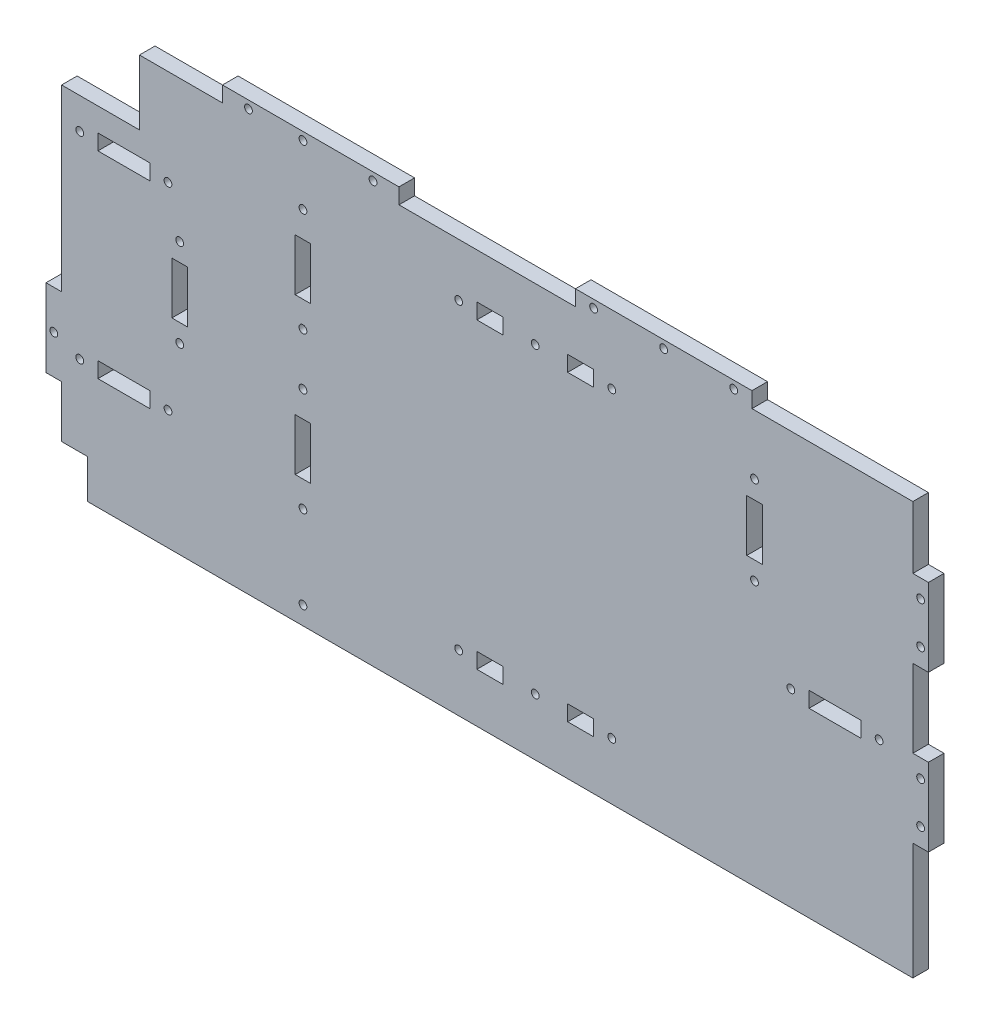
SolidWorks part; units mm, degrees
ref_plane "Plan de face" through (0, 0, 0) normal (0, 0, 1) x (1, 0, 0)
ref_plane "Plan de dessus" through (0, 0, 0) normal (0, 1, 0) x (1, 0, 0)
ref_plane "Plan de droite" through (0, 0, 0) normal (1, 0, 0) x (0, 0, -1)
sketch "Esquisse1" plane through (0, 0, 0) normal (0, 0, 1) x (1, 0, 0)
  line L1 (0, 0) -> (-340, 0)
  line L2 (0, 0) -> (0, 165)
  line L3 (0, 165) -> (-340, 165)
  line L4 (-340, 0) -> (-340, 165)
  dimension "D1" = 165
  dimension "D2" = 340
extrude "Boss.-Extru.1" add sketch "Esquisse1" along normal blind 6
sketch "Esquisse2" plane through (0, 0, 6) normal (0, 0, 1) x (1, 0, 0)
  line L0 (0, 0) -> (0, 165) construction
  line L1 (0, 165) -> (-340, 165) construction
  line L2 (0, 165) -> (0, 135)
  line L4 (0, 135) -> (-6, 135)
  line L5 (-6, 159) -> (-6, 135)
  line L6 (-340, 165) -> (-272, 165)
  line L7 (-340, 165) -> (-340, 65)
  line L8 (-340, 65) -> (-334, 65)
  line L9 (-334, 159) -> (-334, 65)
  line L10 (-70, 129) -> (-64, 129)
  line L11 (-70, 129) -> (-70, 109)
  line L12 (-70, 109) -> (-64, 109)
  line L13 (-334, 159) -> (-272, 159)
  line L14 (-272, 165) -> (-272, 159)
  line L15 (-204, 165) -> (-136, 165)
  line L16 (-204, 165) -> (-204, 159)
  line L17 (-204, 159) -> (-136, 159)
  line L18 (0, 0) -> (0, 165) construction
  line L19 (0, 0) -> (-6, 0)
  line L20 (0, 0) -> (0, 45)
  line L21 (0, 45) -> (-6, 45)
  line L22 (-136, 165) -> (-136, 159)
  line L23 (0, 165) -> (-68, 165)
  line L24 (-340, 0) -> (-334, 0)
  line L25 (-6, 159) -> (-68, 159)
  line L26 (-68, 165) -> (-68, 159)
  line L27 (-64, 129) -> (-64, 109)
  line L28 (-6, 0) -> (-6, 45)
  line L29 (0, 105) -> (-6, 105)
  line L30 (0, 105) -> (0, 75)
  line L31 (0, 75) -> (-6, 75)
  line L32 (-6, 105) -> (-6, 75)
  line L33 (-340, 0) -> (-340, 35)
  line L34 (-340, 35) -> (-334, 35)
  line L35 (-334, 0) -> (-334, 35)
  line L36 (-26, 76) -> (-46, 76)
  line L37 (-26, 76) -> (-26, 70)
  line L38 (-26, 70) -> (-46, 70)
  line L39 (-46, 76) -> (-46, 70)
  dimension "D3" = 6
  dimension "D4" = 62
  dimension "D5" = 68
  dimension "D6" = 68
  dimension "D7" = 24
  dimension "D8" = 6
  dimension "D9" = 70
  dimension "D10" = 6
  dimension "D11" = 6
  dimension "D12" = 6
  dimension "D13" = 6
  dimension "D14" = 68
  dimension "D15" = 6
  dimension "D16" = 30
  dimension "D17" = 36
  dimension "D18" = 6
  dimension "D19" = 20
  dimension "D20" = 30
  dimension "D21" = 30
  dimension "D22" = 100
  dimension "D23" = 6
  dimension "D24" = 20
  dimension "D25" = 6
  dimension "D26" = 26
  dimension "D27" = 89
  dimension "D28" = 30
extrude "Enlèv. mat.-Extru.1" cut sketch "Esquisse2" against normal blind 6
sketch "Esquisse3" plane through (0, 0, 0) normal (0, 0, -1) x (-1, 0, 0)
  line L0 (340, 65) -> (340, 35) construction
  line L1 (238, 109) -> (244, 109)
  line L2 (238, 109) -> (238, 129)
  line L3 (238, 129) -> (244, 129)
  line L4 (244, 109) -> (244, 129)
  line L5 (340, 65) -> (340, 35) construction
  line L6 (340, 65) -> (340, 35) construction
  line L7 (238, 69) -> (244, 69)
  line L8 (238, 69) -> (238, 49)
  line L9 (238, 49) -> (244, 49)
  line L10 (244, 69) -> (244, 49)
  line L11 (204, 165) -> (272, 165) construction
  line L12 (285.5, 77.5) -> (291.5, 77.5)
  line L13 (285.5, 77.5) -> (285.5, 97.5)
  line L14 (285.5, 97.5) -> (291.5, 97.5)
  line L15 (291.5, 77.5) -> (291.5, 97.5)
  line L17 (204, 165) -> (272, 165) construction
  line L18 (300, 49) -> (320, 49)
  line L19 (300, 49) -> (300, 43)
  line L20 (300, 43) -> (320, 43)
  line L21 (320, 49) -> (320, 43)
  line L22 (300, 125) -> (320, 125)
  line L23 (300, 125) -> (300, 119)
  line L24 (300, 119) -> (320, 119)
  line L25 (320, 125) -> (320, 119)
  line L26 (334, 159) -> (304, 159)
  line L27 (334, 159) -> (334, 134)
  line L28 (334, 134) -> (304, 134)
  line L29 (340, 65) -> (340, 35) construction
  line L30 (304, 159) -> (304, 134)
  point P12 (340, 50)
  dimension "D1" = 6
  dimension "D2" = 20
  dimension "D3" = 96
  dimension "D4" = 36
  dimension "D5" = 6
  dimension "D6" = 40
  dimension "D7" = 96
  dimension "D8" = 20
  dimension "D9" = 20
  dimension "D10" = 6
  dimension "D11" = 48.5
  dimension "D12" = 67.5
  dimension "D13" = 6
  dimension "D14" = 20
  dimension "D15" = 20
  dimension "D16" = 40
  dimension "D17" = 6
  dimension "D18" = 70
  dimension "D19" = 20
  dimension "D20" = 20
  dimension "D21" = 30
  dimension "D22" = 25
extrude "Enlèv. mat.-Extru.2" cut sketch "Esquisse3" against normal blind 10
sketch "Esquisse5" plane through (0, 0, 0) normal (0, 0, -1) x (-1, 0, 0)
  line L0 (68, 165) -> (136, 165) construction
  line L1 (129, 141.6) -> (139, 141.6)
  line L2 (129, 141.6) -> (129, 135.6)
  line L3 (129, 135.6) -> (139, 135.6)
  line L4 (139, 141.6) -> (139, 135.6)
  line L5 (164, 135.6) -> (174, 135.6)
  line L6 (164, 135.6) -> (164, 141.6)
  line L7 (164, 141.6) -> (174, 141.6)
  line L8 (174, 135.6) -> (174, 141.6)
  line L10 (129, 25) -> (139, 25)
  line L11 (129, 25) -> (129, 19)
  line L12 (340, 65) -> (340, 35) construction
  line L13 (129, 19) -> (139, 19)
  line L14 (139, 25) -> (139, 19)
  line L15 (68, 165) -> (136, 165) construction
  line L16 (164, 25) -> (174, 25)
  line L17 (164, 25) -> (164, 19)
  line L18 (164, 19) -> (174, 19)
  line L19 (174, 25) -> (174, 19)
  line L20 (204, 165) -> (272, 165) construction
  line L21 (340, 65) -> (340, 35) construction
  line L22 (204, 159) -> (136, 159) construction
  circle A0 centre (151.5, 138.6) radius 1.5
  circle A1 centre (151.5, 22) radius 1.5
  dimension "D9" = 3
  dimension "D14" = 140
  dimension "D21" = 3
  dimension "D22" = 137
  dimension "D1" = 6
  dimension "D2" = 10
  dimension "D3" = 6
  dimension "D4" = 10
  dimension "D5" = 25
  dimension "D6" = 23.4
  dimension "D7" = 23.4
  dimension "D8" = 166
  dimension "D10" = 12.5
  dimension "D11" = 26.4
  dimension "D12" = 6
  dimension "D13" = 140
  dimension "D15" = 25
  dimension "D16" = 12.5
  dimension "D17" = 166
  dimension "D18" = 10
  dimension "D19" = 10
  dimension "D20" = 140
extrude "Enlèv. mat.-Extru.4" cut sketch "Esquisse5" against normal blind 6
sketch "Esquisse7" plane through (0, 0, 0) normal (0, 0, -1) x (-1, 0, 0)
  line L0 (241, 45.9831) -> (241, 125.9831) construction
  line L2 (334, 0) -> (324, 0)
  line L3 (238, 49) -> (244, 49) construction
  line L4 (244, 69) -> (238, 69) construction
  line L5 (238, 109) -> (244, 109) construction
  line L6 (244, 129) -> (238, 129) construction
  line L7 (204, 165) -> (272, 165) construction
  line L8 (272, 159) -> (272, 165) construction
  line L9 (204, 165) -> (204, 159) construction
  line L10 (164, 135.6) -> (174, 135.6) construction
  line L11 (174, 135.6) -> (174, 141.6) construction
  line L12 (139, 141.6) -> (129, 141.6) construction
  line L13 (129, 141.6) -> (129, 135.6) construction
  line L14 (129, 25) -> (129, 19) construction
  line L15 (139, 25) -> (129, 25) construction
  line L16 (164, 19) -> (174, 19) construction
  line L17 (174, 19) -> (174, 25) construction
  line L18 (46, 76) -> (46, 70) construction
  line L19 (46, 70) -> (26, 70) construction
  line L20 (26, 70) -> (26, 76) construction
  line L21 (70, 129) -> (70, 109) construction
  line L22 (70, 109) -> (64, 109) construction
  line L23 (64, 129) -> (70, 129) construction
  line L24 (0, 45) -> (0, 75) construction
  line L25 (0, 45) -> (6, 45) construction
  line L26 (6, 75) -> (0, 75) construction
  line L27 (0, 105) -> (0, 135) construction
  line L28 (0, 105) -> (6, 105) construction
  line L29 (6, 135) -> (0, 135) construction
  line L30 (68, 165) -> (68, 159) construction
  line L31 (68, 165) -> (136, 165) construction
  line L32 (136, 159) -> (136, 165) construction
  line L33 (334, 0) -> (6, 0) construction
  line L34 (238, 69) -> (238, 49) construction
  line L35 (300, 49) -> (300, 43) construction
  line L36 (300, 43) -> (320, 43) construction
  line L37 (320, 49) -> (300, 49) construction
  line L38 (320, 43) -> (320, 49) construction
  line L39 (340, 65) -> (340, 35) construction
  line L40 (334, 35) -> (340, 35) construction
  line L41 (320, 119) -> (320, 125) construction
  line L42 (320, 125) -> (300, 125) construction
  line L43 (300, 125) -> (320, 125) construction
  line L44 (300, 125) -> (300, 119) construction
  line L45 (291.5, 97.5) -> (285.5, 97.5) construction
  line L46 (291.5, 77.5) -> (291.5, 97.5) construction
  line L47 (285.5, 97.5) -> (285.5, 77.5) construction
  line L48 (285.5, 77.5) -> (291.5, 77.5) construction
  line L49 (334, 0) -> (334, 15)
  line L50 (334, 15) -> (324, 15)
  line L51 (324, 0) -> (324, 15)
  circle A0 centre (337, 50) radius 1.5
  circle A1 centre (293, 122) radius 1.5
  circle A2 centre (327, 122) radius 1.5
  circle A3 centre (293, 46) radius 1.5
  circle A4 centre (327, 46) radius 1.5
  circle A5 centre (288.5, 70.5) radius 1.5
  circle A6 centre (288.5, 104.5) radius 1.5
  circle A7 centre (241, 39) radius 1.5
  circle A8 centre (241, 79) radius 1.5
  circle A9 centre (241, 99) radius 1.5
  circle A10 centre (241, 139) radius 1.5
  circle A11 centre (241, 7) radius 1.5
  circle A12 centre (241, 162) radius 1.5
  circle A13 centre (262, 162) radius 1.5
  circle A14 centre (214, 162) radius 1.5
  circle A15 centre (75, 162) radius 1.5
  circle A16 centre (102, 162) radius 1.5
  circle A17 centre (129, 162) radius 1.5
  circle A18 centre (67, 102) radius 1.5
  circle A19 centre (67, 136) radius 1.5
  circle A20 centre (53, 73) radius 1.5
  circle A21 centre (19, 73) radius 1.5
  circle A22 centre (3, 52) radius 1.505
  circle A23 centre (3, 68) radius 1.5
  circle A24 centre (3, 112) radius 1.5
  circle A25 centre (3, 128) radius 1.5
  circle A26 centre (122, 138.6) radius 1.5
  circle A27 centre (181, 138.6) radius 1.5
  circle A28 centre (181, 22) radius 1.5
  circle A29 centre (122, 22) radius 1.5
  point P108 (3, 75)
  point P139 (320, 122)
  dimension "D1" = 3.01
  dimension "D2" = 3
  dimension "D3" = 3
  dimension "D4" = 3
  dimension "D5" = 3
  dimension "D6" = 3
  dimension "D7" = 3
  dimension "D8" = 3
  dimension "D9" = 3
  dimension "D10" = 3
  dimension "D11" = 3
  dimension "D12" = 3
  dimension "D13" = 3
  dimension "D14" = 3
  dimension "D15" = 3
  dimension "D16" = 3
  dimension "D17" = 3
  dimension "D18" = 3
  dimension "D19" = 3
  dimension "D20" = 3
  dimension "D21" = 3
  dimension "D22" = 3
  dimension "D23" = 3
  dimension "D24" = 3
  dimension "D25" = 3
  dimension "D26" = 3
  dimension "D27" = 3
  dimension "D28" = 3
  dimension "D29" = 3
  dimension "D30" = 3
  dimension "D31" = 10
  dimension "D32" = 10
  dimension "D33" = 10
  dimension "D34" = 10
  dimension "D35" = 3
  dimension "D36" = 3
  dimension "D37" = 10
  dimension "D38" = 3
  dimension "D39" = 10
  dimension "D40" = 3
  dimension "D41" = 7
  dimension "D42" = 3
  dimension "D43" = 7
  dimension "D44" = 7
  dimension "D45" = 3
  dimension "D46" = 3
  dimension "D47" = 7
  dimension "D48" = 7
  dimension "D49" = 3
  dimension "D50" = 7
  dimension "D51" = 3
  dimension "D52" = 3
  dimension "D53" = 7
  dimension "D54" = 3
  dimension "D55" = 7
  dimension "D56" = 3
  dimension "D57" = 7
  dimension "D58" = 3
  dimension "D59" = 7
  dimension "D60" = 3
  dimension "D61" = 7
  dimension "D62" = 3
  dimension "D63" = 7
  dimension "D64" = 7
  dimension "D65" = 3
  dimension "D66" = 3
  dimension "D67" = 34
  dimension "D68" = 7
  dimension "D69" = 3
  dimension "D70" = 7
  dimension "D72" = 7
  dimension "D73" = 3
  dimension "D74" = 3
  dimension "D75" = 7
  dimension "D76" = 3
  dimension "D77" = 15
  dimension "D78" = 7
  dimension "D79" = 3
  dimension "D80" = 3
  dimension "D81" = 7
  dimension "D82" = 7
  dimension "D83" = 3
  dimension "D84" = 3
  dimension "D85" = 7
  dimension "D71" = 3
  dimension "D86" = 10
  dimension "D87" = 15
extrude "Enlèv. mat.-Extru.7" cut sketch "Esquisse7" against normal through all
sketch "Esquisse8" plane through (0, 0, 0) normal (0, 0, -1) x (-1, 0, 0)
  circle A0 centre (3, 52) radius 2.995
  circle A1 centre (3, 68) radius 2.995
  circle A2 centre (19, 73) radius 3
  circle A3 centre (3, 112) radius 2.995
  circle A4 centre (3, 128) radius 2.995
  circle A5 centre (53, 73) radius 3
  circle A6 centre (67, 102) radius 3
  circle A7 centre (67, 136) radius 3
  circle A8 centre (75, 162) radius 2.995
  circle A9 centre (102, 162) radius 2.995
  circle A10 centre (129, 162) radius 2.995
  circle A11 centre (122, 138.6) radius 3
  circle A12 centre (151.5, 138.6) radius 3
  circle A13 centre (181, 138.6) radius 3
  circle A14 centre (181, 22) radius 3
  circle A15 centre (151.5, 22) radius 3
  circle A16 centre (122, 22) radius 3
  circle A17 centre (214, 162) radius 2.995
  circle A18 centre (241, 162) radius 2.995
  circle A19 centre (262, 162) radius 2.995
  circle A20 centre (241, 139) radius 3
  circle A21 centre (241, 99) radius 3
  circle A22 centre (241, 79) radius 3
  circle A23 centre (241, 39) radius 3
  circle A24 centre (241, 7) radius 3
  circle A25 centre (337, 50) radius 2.995
  circle A26 centre (327, 46) radius 3
  circle A27 centre (293, 46) radius 3
  circle A28 centre (288.5, 70.5) radius 3
  circle A29 centre (288.5, 104.5) radius 3
  circle A30 centre (293, 122) radius 3
  circle A31 centre (327, 122) radius 3
  dimension "D1" = 5.99
  dimension "D2" = 5.99
  dimension "D3" = 5.99
  dimension "D4" = 5.99
  dimension "D5" = 6
  dimension "D6" = 6
  dimension "D7" = 6
  dimension "D8" = 6
  dimension "D9" = 5.99
  dimension "D10" = 5.99
  dimension "D11" = 5.99
  dimension "D12" = 6
  dimension "D13" = 6
  dimension "D14" = 6
  dimension "D15" = 6
  dimension "D16" = 6
  dimension "D17" = 6
  dimension "D18" = 5.99
  dimension "D19" = 5.99
  dimension "D20" = 5.99
  dimension "D21" = 6
  dimension "D22" = 6
  dimension "D23" = 6
  dimension "D24" = 6
  dimension "D25" = 6
  dimension "D26" = 6
  dimension "D27" = 6
  dimension "D28" = 6
  dimension "D29" = 6
  dimension "D30" = 6
  dimension "D31" = 5.99
  dimension "D32" = 6
extrude "Enlèv. mat.-Extru.9" cut sketch "Esquisse8" against normal blind 3
